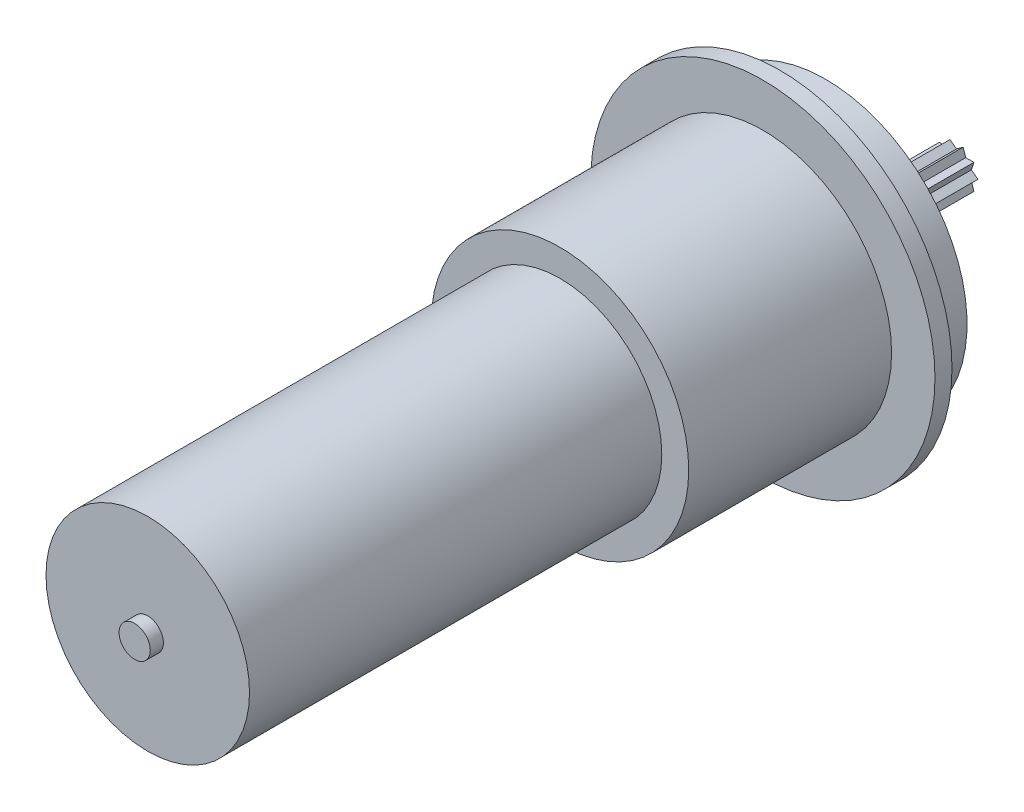
SolidWorks part; units mm, degrees
ref_plane "Front Plane" through (0, 0, 0) normal (0, 0, 1) x (1, 0, 0)
ref_plane "Top Plane" through (0, 0, 0) normal (0, 1, 0) x (1, 0, 0)
ref_plane "Right Plane" through (0, 0, 0) normal (1, 0, 0) x (0, 0, -1)
sketch "Sketch1" plane through (0, 0, 0) normal (0, 0, 1) x (1, 0, 0)
  circle A0 centre (0, 0) radius 49.9618
extrude "Boss-Extrude1" add sketch "Sketch1" along normal blind 78.74 contours A0
sketch "Sketch2" plane through (0, 0, 0) normal (0, 0, -1) x (-1, 0, 0)
  circle A0 centre (0, 0) radius 66.802
extrude "Boss-Extrude2" add sketch "Sketch2" along normal blind 6.604
sketch "Sketch3" plane through (0, 0, -6.604) normal (0, 0, -1) x (-1, 0, 0)
  circle A0 centre (0, 0) radius 54.864
extrude "Boss-Extrude3" add sketch "Sketch3" along normal blind 17.78
sketch "Sketch4" plane through (0, 0, -24.384) normal (0, 0, -1) x (-1, 0, 0)
  circle A0 centre (0, 0) radius 11.878
extrude "Boss-Extrude4" add sketch "Sketch4" along normal blind 12.7
sketch "Sketch5" plane through (0, 0, -37.084) normal (0, 0, -1) x (-1, 0, 0)
  line L10 (8.3153, 0) -> (5.7458, 1.8669)
  line L11 (5.7458, 1.8669) -> (6.7272, 4.8876)
  line L12 (6.7272, -4.8876) -> (5.7458, -1.8669)
  line L17 (5.7458, -1.8669) -> (8.3153, 0)
  line L18 (2.5696, -7.9084) -> (3.5511, -4.8876)
  line L19 (3.5511, -4.8876) -> (6.7272, -4.8876)
  line L20 (-2.5696, -7.9084) -> (0, -6.0414)
  line L21 (0, -6.0414) -> (2.5696, -7.9084)
  line L22 (-6.7272, -4.8876) -> (-3.5511, -4.8876)
  line L23 (-3.5511, -4.8876) -> (-2.5696, -7.9084)
  line L24 (-8.3153, 0) -> (-5.7458, -1.8669)
  line L25 (-5.7458, -1.8669) -> (-6.7272, -4.8876)
  line L26 (-6.7272, 4.8876) -> (-5.7458, 1.8669)
  line L27 (-5.7458, 1.8669) -> (-8.3153, 0)
  line L28 (-2.5696, 7.9084) -> (-3.5511, 4.8876)
  line L29 (-3.5511, 4.8876) -> (-6.7272, 4.8876)
  line L30 (2.5696, 7.9084) -> (0, 6.0414)
  line L31 (0, 6.0414) -> (-2.5696, 7.9084)
  line L32 (6.7272, 4.8876) -> (3.5511, 4.8876)
  line L33 (3.5511, 4.8876) -> (2.5696, 7.9084)
  dimension "D1" = 10
extrude "Boss-Extrude5" add sketch "Sketch5" along normal blind 38.1
sketch "Sketch7" plane through (0, 0, 78.74) normal (0, 0, 1) x (1, 0, 0)
  circle A0 centre (0, 0) radius 39.497
extrude "Boss-Extrude6" add sketch "Sketch7" along normal blind 160.02
sketch "Sketch8" plane through (0, 0, 238.76) normal (0, 0, 1) x (1, 0, 0)
  circle A0 centre (0, 0) radius 6.0587
extrude "Boss-Extrude7" add sketch "Sketch8" along normal blind 5.08
